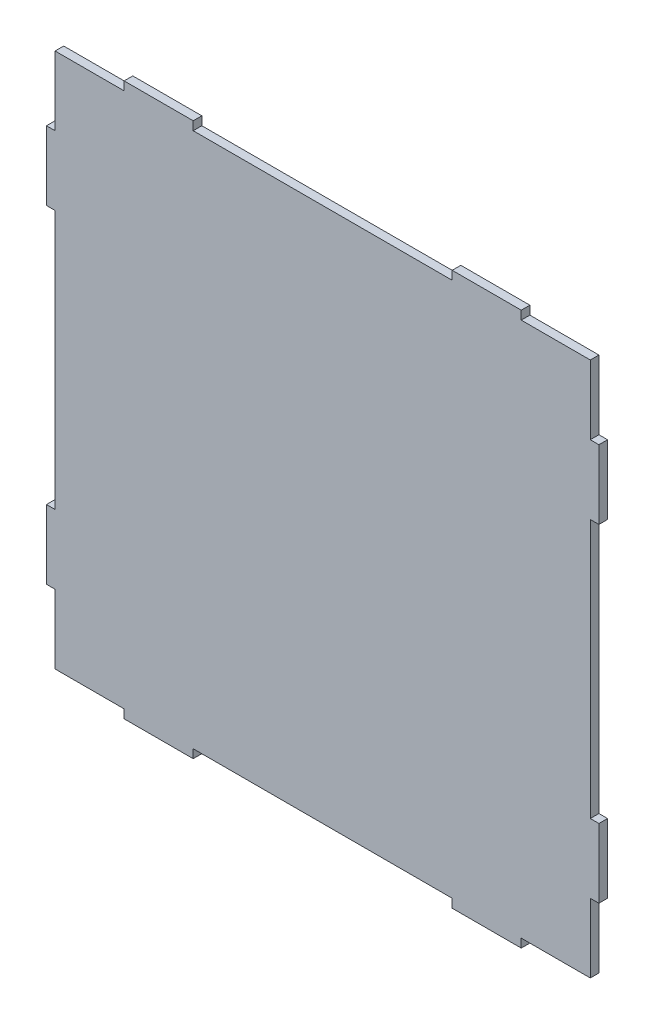
SolidWorks part; units mm, degrees
ref_plane "Front Plane" through (0, 0, 0) normal (0, 0, 1) x (1, 0, 0)
ref_plane "Top Plane" through (0, 0, 0) normal (0, 1, 0) x (1, 0, 0)
ref_plane "Right Plane" through (0, 0, 0) normal (1, 0, 0) x (0, 0, -1)
sketch "Sketch2" plane through (0, 0, 0) normal (0, 0, 1) x (1, 0, 0)
  line L0 (-50.8, 70.0149) -> (-25.4, 70.0149)
  line L1 (-25.4, 70.0149) -> (-25.4, 73.1899)
  line L2 (-25.4, 73.1899) -> (0, 73.1899)
  line L3 (0, 73.1899) -> (0, 70.0149)
  line L4 (0, 70.0149) -> (95.25, 70.0149)
  line L5 (95.25, 70.0149) -> (95.25, 73.1899)
  line L6 (95.25, 73.1899) -> (120.65, 73.1899)
  line L7 (120.65, 73.1899) -> (120.65, 70.0149)
  line L8 (120.65, 70.0149) -> (146.05, 70.0149)
  line L9 (146.05, 70.0149) -> (146.05, 44.6149)
  line L10 (146.05, 44.6149) -> (149.225, 44.6149)
  line L11 (149.225, 44.6149) -> (149.225, 19.2149)
  line L12 (149.225, 19.2149) -> (146.05, 19.2149)
  line L13 (146.05, 19.2149) -> (146.05, -76.0351)
  line L14 (146.05, -76.0351) -> (149.225, -76.0351)
  line L15 (149.225, -76.0351) -> (149.225, -101.4351)
  line L16 (149.225, -101.4351) -> (146.05, -101.4351)
  line L17 (146.05, -101.4351) -> (146.05, -126.8351)
  line L18 (-50.8, 70.0149) -> (-50.8, 44.6149)
  line L19 (-50.8, 44.6149) -> (-53.975, 44.6149)
  line L20 (-53.975, 44.6149) -> (-53.975, 19.2149)
  line L21 (-53.975, 19.2149) -> (-50.8, 19.2149)
  line L22 (-50.8, 19.2149) -> (-50.8, -76.0351)
  line L23 (-50.8, -76.0351) -> (-53.975, -76.0351)
  line L24 (-53.975, -76.0351) -> (-53.975, -101.4351)
  line L25 (-53.975, -101.4351) -> (-50.8, -101.4351)
  line L26 (-50.8, -101.4351) -> (-50.8, -126.8351)
  line L27 (-50.8, -126.8351) -> (-25.4, -126.8351)
  line L28 (-25.4, -126.8351) -> (-25.4, -130.0101)
  line L29 (-25.4, -130.0101) -> (0, -130.0101)
  line L30 (0, -130.0101) -> (0, -126.8351)
  line L31 (0, -126.8351) -> (95.25, -126.8351)
  line L32 (95.25, -126.8351) -> (95.25, -130.0101)
  line L33 (95.25, -130.0101) -> (120.65, -130.0101)
  line L34 (120.65, -130.0101) -> (120.65, -126.8351)
  line L35 (120.65, -126.8351) -> (146.05, -126.8351)
  dimension "D1" = 25.4
  dimension "D2" = 25.4
  dimension "D3" = 95.25
  dimension "D4" = 3.175
  dimension "D5" = 95.25
  dimension "D6" = 95.25
  dimension "D7" = 95.25
extrude "Boss-Extrude1" add sketch "Sketch2" along normal blind 3.175
